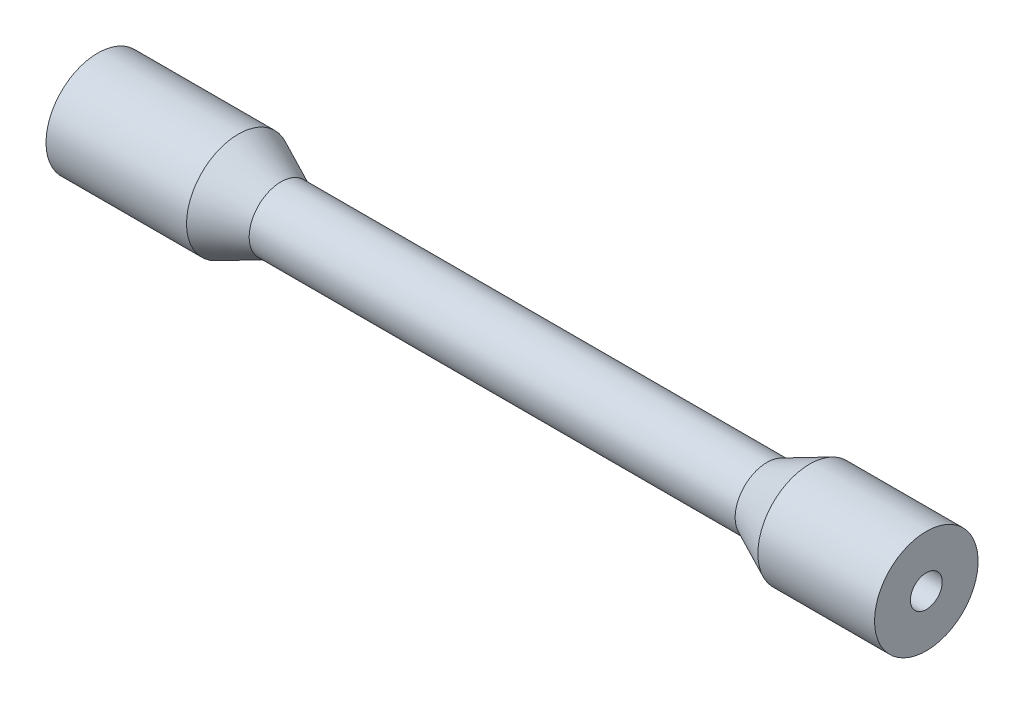
SolidWorks part; units mm, degrees
ref_plane "前视基准面" through (0, 0, 0) normal (0, 0, 1) x (1, 0, 0)
ref_plane "上视基准面" through (0, 0, 0) normal (0, 1, 0) x (1, 0, 0)
ref_plane "右视基准面" through (0, 0, 0) normal (1, 0, 0) x (0, 0, -1)
other "Configuration Table"
sketch "草图1" plane through (0, 0, 0) normal (1, 0, 0) x (0, 0, -1)
  circle A0 centre (0, 0) radius 1
  circle A1 centre (0, 0) radius 3.25
  dimension "D1" = 2
  dimension "D2" = 6.5
extrude "凸台-拉伸1" add sketch "草图1" along normal mid plane 52
sketch "草图2" plane through (0, 0, 0) normal (0, 0, 1) x (1, 0, 0)
  line L5 (26, 3.25) -> (-26, 3.25) construction
  line L6 (-26, 0) -> (26, 0) construction
  line L7 (-26, 3.25) -> (-26, -3.25) construction
  line L8 (26, -3.25) -> (26, 3.25) construction
  line L9 (-17.1806, 3.25) -> (18.6806, 3.25)
  line L10 (-17.1806, 3.25) -> (-14.5, 2)
  line L11 (-14.5, 2) -> (16, 2)
  line L12 (18.6806, 3.25) -> (16, 2)
  line L13 (0.75, 3.25) -> (0.75, 2) construction
  dimension "D1" = 155
  dimension "D2" = 4
  dimension "D3" = 30.5
  dimension "D4" = 10
revolve "切除-旋转1" cut sketch "草图2" angle 360 about L6
